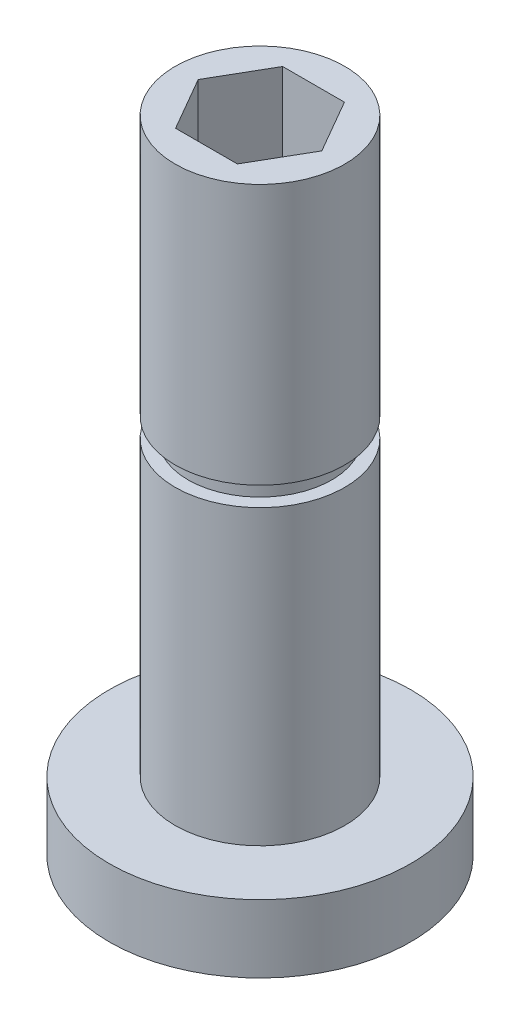
SolidWorks part; units mm, degrees
ref_plane "Front" through (0, 0, 0) normal (0, 0, 1) x (1, 0, 0)
ref_plane "Top" through (0, 0, 0) normal (0, 1, 0) x (1, 0, 0)
ref_plane "Right" through (0, 0, 0) normal (1, 0, 0) x (0, 0, -1)
sketch "Sketch1" plane through (0, 0, 0) normal (0, 1, 0) x (1, 0, 0)
  circle A0 centre (0, 0) radius 8.89
  dimension "D1" = 17.78
extrude "Traingular base (simplified to circle here)" add sketch "Sketch1" along normal blind 4
sketch "Sketch2" plane through (0, 4, 0) normal (0, 1, 0) x (1, 0, 0)
  circle A0 centre (0, 0) radius 5
  dimension "D1" = 10
extrude "Drive shaft" add sketch "Sketch2" along normal blind 33.782
ref_plane "Plane1" through (0, 21.272, 0) normal (0, 1, 0) x (1, 0, 0)
sketch "Sketch4" plane through (0, 21.272, 0) normal (0, 1, 0) x (1, 0, 0)
  circle A0 centre (0, 0) radius 5 construction
  circle A1 centre (0, 0) radius 5
  circle A2 centre (0, 0) radius 4.238
  dimension "D1" = 0.762
extrude "Retaining ring slot" cut sketch "Sketch4" along normal blind 1.143
sketch "Sketch5" plane through (0, 37.782, 0) normal (0, 1, 0) x (1, 0, 0)
  line L1 (3.6449, 0) -> (1.8224, 3.1566)
  line L2 (1.8224, 3.1566) -> (-1.8224, 3.1566)
  line L3 (-1.8224, 3.1566) -> (-3.6449, 0)
  line L4 (-3.6449, 0) -> (-1.8225, -3.1566)
  line L5 (-1.8225, -3.1566) -> (1.8224, -3.1566)
  line L6 (1.8224, -3.1566) -> (3.6449, 0)
  circle A0 centre (0, 0) radius 3.6449 construction
  dimension "D1" = 7.2898
extrude "Hex slot" cut sketch "Sketch5" against normal blind 12.7
